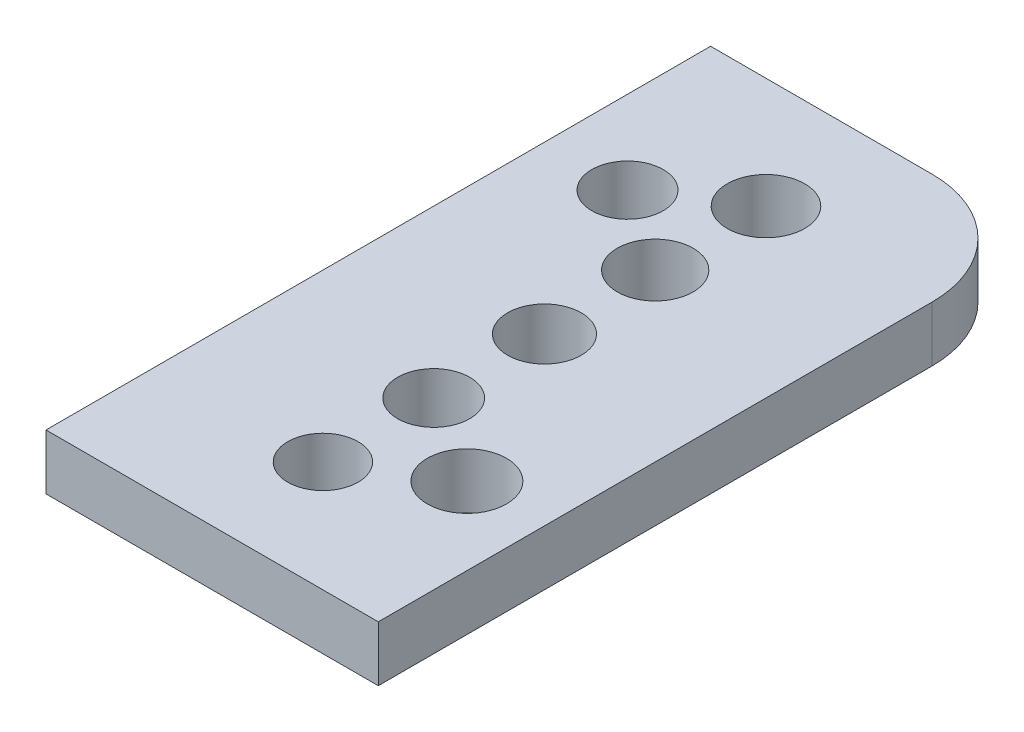
SolidWorks part; units mm, degrees
ref_plane "Plan de face" through (0, 0, 0) normal (0, 0, 1) x (1, 0, 0)
ref_plane "Plan de dessus" through (0, 0, 0) normal (0, 1, 0) x (1, 0, 0)
ref_plane "Plan de droite" through (0, 0, 0) normal (1, 0, 0) x (0, 0, -1)
sketch "Esquisse1" plane through (0, 0, 0) normal (0, 1, 0) x (1, 0, 0)
  line L1 (-15, 30) -> (15, 30)
  line L2 (-15, 30) -> (-15, -30)
  line L3 (-15, -30) -> (15, -30)
  line L4 (15, 30) -> (15, -30)
  line L5 (-15, 30) -> (15, -30) construction
  line L6 (-15, -30) -> (15, 30) construction
  point P0 (0, 0)
  point P5 (0, 0)
  dimension "D1" = 60
  dimension "D2" = 30
extrude "Boss.-Extru.1" add sketch "Esquisse1" along normal blind 5
sketch "Esquisse2" plane through (0, 5, 0) normal (0, 1, 0) x (1, 0, 0)
  line L0 (-15, -30) -> (15, -30) construction
  circle A0 centre (0, -20) radius 3.175
  circle A1 centre (0, -10) radius 3.25
  circle A2 centre (0, 0) radius 3.325
  circle A3 centre (0, 10) radius 3.425
  circle A4 centre (0, 20) radius 3.5
  circle A5 centre (8, -15) radius 3.575
  circle A6 centre (-7.5, 15) radius 3.225
  point P17 (0, 0)
  point P18 (0, 0)
  dimension "D1" = 6.35
  dimension "D2" = 6.5
  dimension "D3" = 6.65
  dimension "D4" = 6.85
  dimension "D9" = 7
  dimension "D11" = 7.15
  dimension "D14" = 6.45
  dimension "D5" = 10
  dimension "D6" = 10
  dimension "D7" = 10
  dimension "D8" = 10
  dimension "D10" = 10
  dimension "D12" = 8
  dimension "D13" = 5
  dimension "D15" = 5
  dimension "D16" = 7.5
extrude "Enlèv. mat.-Extru.1" cut sketch "Esquisse2" against normal up to next
fillet "Congé1" radius 10 1 edges at (15, 2.5, -30)
